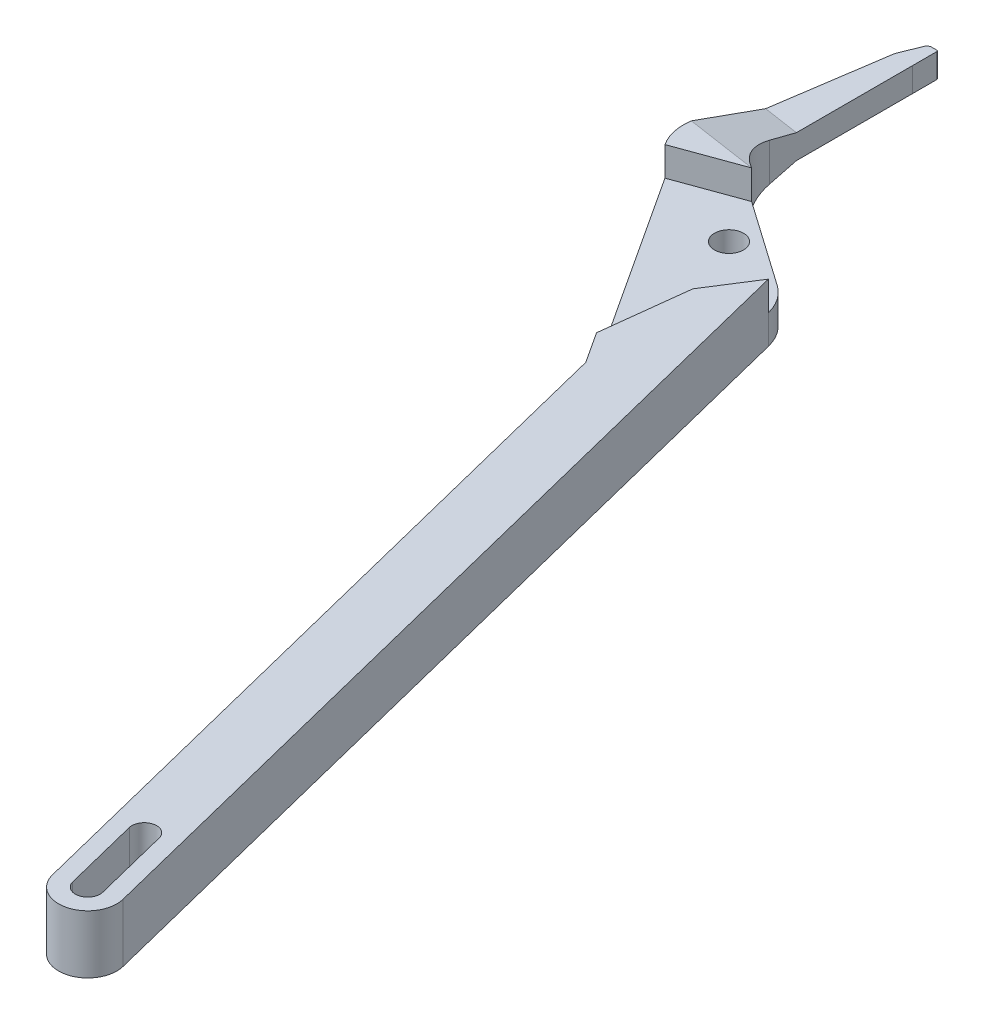
SolidWorks part; units mm, degrees
material "6061-T6 (SS)"
ref_plane "Front Plane" through (0, 0, 0) normal (0, 0, 1) x (1, 0, 0)
ref_plane "Top Plane" through (0, 0, 0) normal (0, 1, 0) x (1, 0, 0)
ref_plane "Right Plane" through (0, 0, 0) normal (1, 0, 0) x (0, 0, -1)
sketch "Sketch1" plane through (0, 0, 0) normal (0, 1, 0) x (1, 0, 0)
  line L0 (4.5666, -9.3015) -> (-20.0079, 7.9058)
  line L1 (-19.4457, 11.6676) -> (-14.0517, 47.76)
  line L2 (-13.8701, 48.4307) -> (-12.2514, 52.4773)
  line L3 (-11.323, 53.1059) -> (-10.25, 53.1059)
  line L4 (-10, 52.8559) -> (-10, 18.3116)
  line L5 (-5.7358, 10.1201) -> (12.7996, -2.8585)
  line L9 (16.7668, -8.6308) -> (60.9657, -185.9031)
  line L10 (60.9657, -185.9031) -> (49.3222, -188.8062)
  line L11 (49.3222, -188.8062) -> (4.5666, -9.3015)
  line L12 (-17.9281, 4.7213) -> (12.8013, -42.3291)
  line L13 (55.1439, -187.3546) -> (51.2732, -171.8299) construction
  line L14 (52.6697, -187.9715) -> (48.7989, -172.4468)
  line L15 (57.6182, -186.7377) -> (53.7474, -171.213)
  circle A0 centre (0, 0) radius 3
  circle A1 centre (55.1439, -187.3546) radius 6
  arc A2 (52.6697, -187.9715) -> (57.6182, -186.7377) centre (55.1439, -187.3546) ccw
  arc A3 (53.7474, -171.213) -> (48.7989, -172.4468) centre (51.2732, -171.8299) ccw
  arc A4 (-10.25, 53.1059) -> (-10, 52.8559) centre (-10.25, 52.8559) cw
  arc A5 (-12.2514, 52.4773) -> (-11.323, 53.1059) centre (-11.323, 52.1059) cw
  arc A6 (-14.0517, 47.76) -> (-13.8701, 48.4307) centre (-11.0847, 47.3166) cw
  arc A7 (-10, 18.3116) -> (-5.7358, 10.1201) centre (0, 18.3116) ccw
  arc A8 (12.7996, -2.8585) -> (16.7668, -8.6308) centre (7.0638, -11.05) cw
  arc A9 (-17.9281, 4.7213) -> (-19.4457, 11.6676) centre (-9.5556, 10.1895) cw
  point P13 (53.2086, -179.5923)
  point P22 (-10, 53.1059)
  point P25 (-12, 53.1059)
  point P28 (-14, 48.1059)
  point P32 (-10, 13.1059)
  dimension "D7" = 6
  dimension "D19" = 12
  dimension "D20" = 2.55
  dimension "D17" = 0.25
  dimension "D23" = 1
  dimension "D24" = 3
  dimension "D26" = 10
  dimension "D2" = 2
  dimension "D3" = 2
  dimension "D4" = 5
  dimension "D5" = 8.5
  dimension "D6" = 40
  dimension "D8" = 5
  dimension "D9" = 10
  dimension "D10" = 125
  dimension "D11" = 90
  dimension "D12" = 12
  dimension "D13" = 139
  dimension "D14" = 10
  dimension "D15" = 30
  dimension "D16" = 40.2001
  dimension "D18" = 185
  dimension "D21" = 180
  dimension "D22" = 16
  dimension "D25" = 60
extrude "Boss-Extrude2" add sketch "Sketch1" along normal blind 12 contours A9 L0 L11 A1 L14 A3 L15 L9 A8 L5 A7 L4 A4 L3 A5 L2 A6 L1 A0 | L14 A1 L10 | L10 A1 L15 | A2 L10 A1 | A9 L12 L11 L0
sketch "Sketch3" plane through (-20.7265, 0, -3.0976) normal (-0.989, 0, -0.1478) x (-0.1478, 0, 0.989)
  line L0 (0, 0) -> (-57.1585, 0)
  line L1 (-8.6652, 6) -> (-57.1585, 6)
  line L2 (-8.6652, 12) -> (-8.6652, 0) construction
  line L3 (-57.1585, 0) -> (-57.1585, 12)
  line L4 (-8.6652, 6) -> (-8.6652, 0)
  line L5 (-8.6652, 0) -> (-22.1585, 3.5)
  line L6 (-22.1585, 3.5) -> (-57.1585, 3.5)
  line L7 (0, 12) -> (-57.1585, 12)
  line L8 (-8.6652, 12) -> (-22.1585, 8.5)
  line L9 (-22.1585, 8.5) -> (-57.1585, 8.5)
  line L10 (0, 0) -> (0, 12)
  line M9 (-45.1584, 0) -> (-8.6652, 0)
  line M11 (-8.6652, 12) -> (-45.1584, 12)
  line M12 (-45.1584, 12) -> (-45.1584, 0)
  dimension "D1" = 48.4933
  dimension "D2" = 2.5
  dimension "D3" = 35
extrude "Cut-Extrude1" cut sketch "Sketch3" against normal through all contours L5 L6 M12 M9 | L9 L8 M11 M12 | L9 L7 L3 M12 | L6 L3 L0 M12
sketch "Sketch4" plane through (0, 12, 0) normal (0, 1, 0) x (1, 0, 0)
  line L2 (-4.8253, 9.4826) -> (-17.9281, 4.7213)
  line L3 (-17.9281, 4.7213) -> (12.8013, -42.3291)
  line L4 (12.8013, -42.3291) -> (16.7668, -8.6308)
  line L5 (16.7668, -8.6308) -> (17.4322, -2.9762)
  line L6 (17.4322, -2.9762) -> (-4.8253, 9.4826)
  line L7 (8.6208, -35.9281) -> (12.8033, -0.3852)
  line L8 (16.7668, -8.6308) -> (10.712, -18.1567)
  circle M5 centre (0, 0) radius 3
  line M9 (-17.9281, 4.7213) -> (12.8013, -42.3291)
  arc M13 (16.7668, -8.6308) -> (12.7996, -2.8585) centre (7.0638, -11.05) ccw
  line M14 (12.7996, -2.8585) -> (-4.8253, 9.4826)
  dimension "D1" = 5.6546
  dimension "D2" = 0
  dimension "D3" = 4.9
extrude "Cut-Extrude4" cut sketch "Sketch4" against normal blind 6 contours L7 L2 M9 M13 M14 M5 | L8 L7 M13
sketch "Sketch5" plane through (-10, 0, 0) normal (1, 0, 0) x (0, 0, -1)
  line L0 (47.8559, 3.5) -> (47.8559, 8.5)
  line L1 (52.8559, 3.5) -> (23.8992, 3.5) construction
  line L2 (52.8559, 8.5) -> (23.8992, 8.5) construction
  line L3 (52.8559, 8.5) -> (52.8559, 3.5) construction
  dimension "D1" = 5
split line "Split Line1"
equation "\"weightkg\"= \"SW-Mass\" / 1000"
